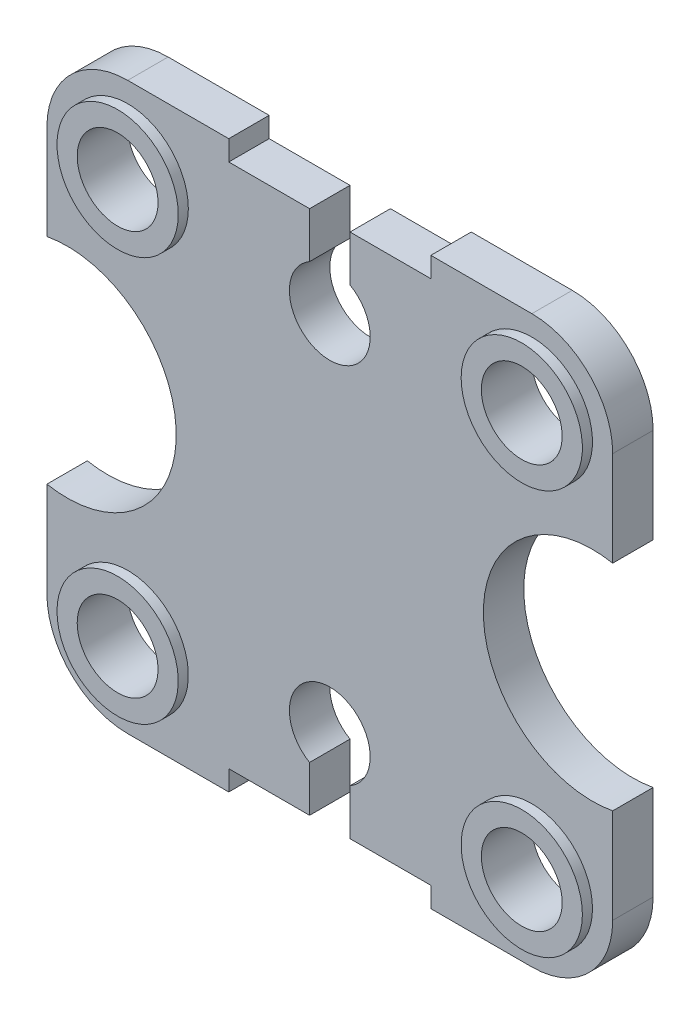
SolidWorks part; units mm, degrees
ref_plane "Front Plane" through (0, 0, 0) normal (0, 0, 1) x (1, 0, 0)
ref_plane "Top Plane" through (0, 0, 0) normal (0, 1, 0) x (1, 0, 0)
ref_plane "Right Plane" through (0, 0, 0) normal (1, 0, 0) x (0, 0, -1)
sketch "Sketch1" plane through (0, 0, 0) normal (0, 0, 1) x (1, 0, 0)
  line L0 (-140, 0) -> (76, 0) construction
  line L1 (-100, 140) -> (100, 140)
  line L2 (-140, 100) -> (-140, 53.066)
  line L3 (-100, -140) -> (100, -140)
  line L4 (140, 100) -> (140, 53.066)
  line L5 (-140, -53.066) -> (-140, -100)
  line L6 (140, -53.066) -> (140, -100)
  line L7 (0, 140) -> (0, -140) construction
  arc A0 (100, -140) -> (140, -100) centre (100, -100) ccw
  arc A1 (-100, -140) -> (-140, -100) centre (-100, -100) cw
  arc A2 (140, 100) -> (100, 140) centre (100, 100) ccw
  arc A3 (-140, 100) -> (-100, 140) centre (-100, 100) cw
  arc A4 (-140, -53.066) -> (-140, 53.066) centre (-130, 0) ccw
  arc A5 (140, -53.066) -> (140, 53.066) centre (130, 0) cw
  point P0 (0, 0)
  dimension "D3" = 40
  dimension "D5" = 108
  dimension "D1" = 280
  dimension "D2" = 280
  dimension "D4" = 10
extrude "Boss-Extrude1" add sketch "Sketch1" along normal blind 20
sketch "Sketch2" plane through (0, 0, 20) normal (0, 0, 1) x (1, 0, 0)
  line L0 (0, 140) -> (0, -70) construction
  line L1 (100, 140) -> (-100, 140) construction
  line L2 (-100, -140) -> (100, -140) construction
  line L3 (-76, 0) -> (76, 0) construction
  line L4 (-50, -130) -> (-10, -130)
  line L5 (-50, -140) -> (50, -140)
  line L6 (-50, -130) -> (-50, -140)
  line L7 (50, -130) -> (50, -140)
  line L8 (140, -100) -> (140, -53.066) construction
  line L9 (-10, -130) -> (-10, -107.3205)
  line L10 (10, -130) -> (10, -107.3205)
  line L11 (10, -130) -> (50, -130)
  line L12 (10, 130) -> (50, 130)
  line L13 (10, 130) -> (10, 107.3205)
  line L14 (-10, 130) -> (-10, 107.3205)
  line L15 (50, 130) -> (50, 140)
  line L16 (-50, 130) -> (-50, 140)
  line L17 (-50, 140) -> (50, 140)
  line L18 (-50, 130) -> (-10, 130)
  arc A0 (-140, -53.066) -> (-140, 53.066) centre (-130, 0) ccw construction
  arc A1 (140, 53.066) -> (140, -53.066) centre (130, 0) ccw construction
  arc A2 (10, -107.3205) -> (-10, -107.3205) centre (0, -90) ccw
  arc A3 (10, 107.3205) -> (-10, 107.3205) centre (0, 90) cw
  point P21 (0, 0)
  point P24 (0, 0)
  dimension "D4" = 40
  dimension "D1" = 10
  dimension "D2" = 100
  dimension "D3" = 50
  dimension "D5" = 20
  dimension "D6" = 22.6795
  dimension "D7" = 90
extrude "Cut-Extrude1" cut sketch "Sketch2" against normal blind 20
sketch "Sketch3" plane through (0, 0, 20) normal (0, 0, 1) x (1, 0, 0)
  line L0 (0, -70) -> (0, 70) construction
  line L1 (314.8902, 0) -> (-314.8902, 0) construction
  arc A0 (10, -107.3205) -> (-10, -107.3205) centre (0, -90) ccw construction
  circle A2 centre (100, -100) radius 20
  circle A3 centre (-100, -100) radius 20
  circle A4 centre (-100, 100) radius 20
  circle A5 centre (100, 100) radius 20
  point P4 (0, 0)
  point P8 (0, 0)
  point P21 (129.1224, 0)
  dimension "D3" = 40
  dimension "D1" = 100
  dimension "D2" = 100
extrude "Cut-Extrude2" cut sketch "Sketch3" against normal blind 20
sketch "Sketch5" plane through (0, 0, 20) normal (0, 0, 1) x (1, 0, 0)
  line L0 (0, 167.0507) -> (0, -164.7402) construction
  line L1 (-165.4333, 0) -> (214.4164, 0) construction
  circle A0 centre (-100, 100) radius 30
  circle A1 centre (100, 100) radius 30
  circle A2 centre (100, -100) radius 30
  circle A3 centre (-100, -100) radius 30
  dimension "D1" = 60
extrude "Boss-Extrude2" add sketch "Sketch5" along normal blind 5
sketch "Sketch7" plane through (0, 0, 20) normal (0, 0, 1) x (1, 0, 0)
  line L0 (0, 164.7402) -> (0, -186.9212) construction
  line L1 (-197.3185, 0) -> (227.8174, 0) construction
  circle A2 centre (-100, 100) radius 20
  circle A3 centre (100, 100) radius 20
  circle A4 centre (100, -100) radius 20
  circle A5 centre (-100, -100) radius 20
  dimension "D1" = 40
extrude "Cut-Extrude5" cut sketch "Sketch7" along normal blind 5
